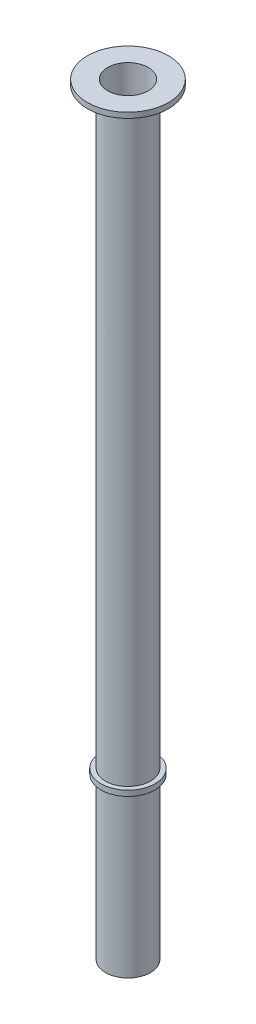
SolidWorks part; units mm, degrees
ref_plane "Front Plane" through (0, 0, 0) normal (0, 0, 1) x (1, 0, 0)
ref_plane "Top Plane" through (0, 0, 0) normal (0, 1, 0) x (1, 0, 0)
ref_plane "Right Plane" through (0, 0, 0) normal (1, 0, 0) x (0, 0, -1)
sketch "Sketch1" plane through (0, 0, 0) normal (0, 1, 0) x (1, 0, 0)
  circle A0 centre (0, 0) radius 11.25
  circle A1 centre (0, 0) radius 12.5
  dimension "D1" = 25
  dimension "D2" = 22.5
extrude "Boss-Extrude1" add sketch "Sketch1" along normal mid plane 420
sketch "Sketch2" plane through (0, 210, 0) normal (0, 1, 0) x (1, 0, 0)
  circle A0 centre (0, 0) radius 22.5
  circle A1 centre (0, 0) radius 11.25
  dimension "D1" = 45
extrude "Boss-Extrude2" add sketch "Sketch2" along normal blind 3
ref_plane "Plane1" through (0, -118, 0) normal (0, -1, 0) x (-1, 0, 0)
sketch "Sketch3" plane through (0, -118, 0) normal (0, -1, 0) x (-1, 0, 0)
  circle A0 centre (0, 0) radius 15
  circle A1 centre (0, 0) radius 11.25
  dimension "D1" = 30
extrude "Boss-Extrude3" add sketch "Sketch3" along normal blind 3
